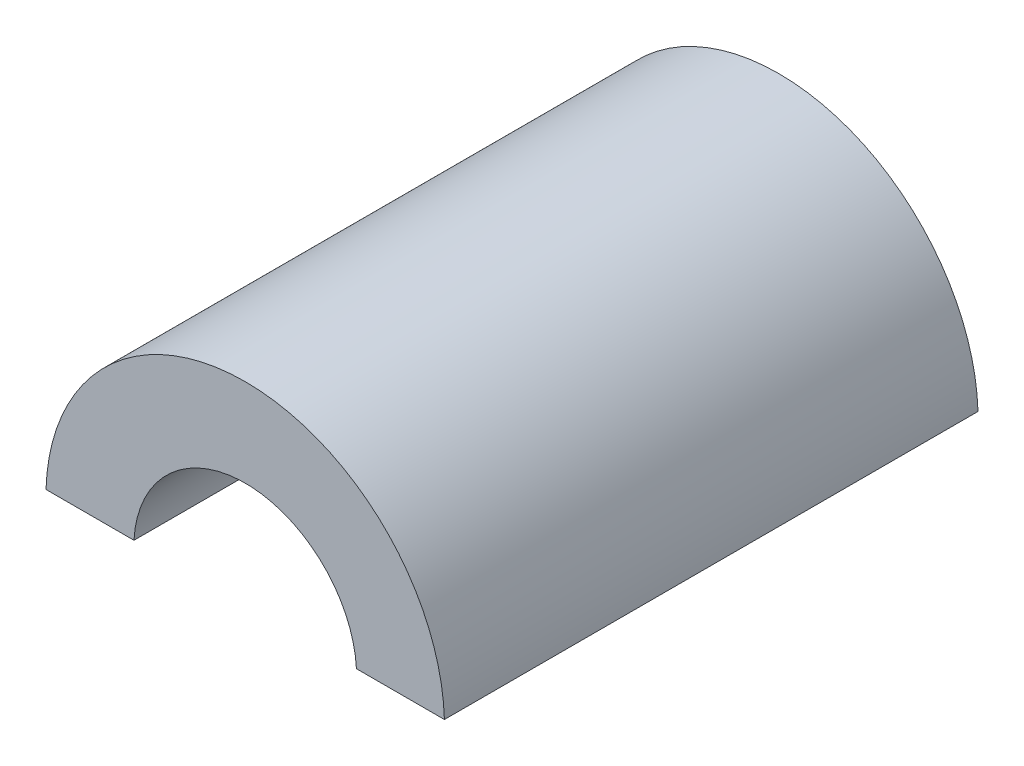
SolidWorks part; units mm, degrees
ref_plane "Front" through (0, 0, 0) normal (0, 0, 1) x (1, 0, 0)
ref_plane "Top" through (0, 0, 0) normal (0, 1, 0) x (1, 0, 0)
ref_plane "Right" through (0, 0, 0) normal (1, 0, 0) x (0, 0, -1)
sketch "Sketch1" plane through (0, 0, 0) normal (0, 0, 1) x (1, 0, 0)
  line L0 (-31.75, 0) -> (31.75, 0) construction
  line L1 (-31.7342, 1) -> (-17.7218, 1)
  line L2 (-31.75, 1) -> (31.75, 1) construction
  line L3 (17.7218, 1) -> (31.7342, 1)
  arc A0 (31.7342, 1) -> (-31.7342, 1) centre (0, 0) ccw
  arc A1 (17.7218, 1) -> (-17.7218, 1) centre (0, 0) ccw
  dimension "D1" = 35.5
  dimension "D2" = 63.5
  dimension "D3" = 1
extrude "Boss-Extrude1" add sketch "Sketch1" along normal blind 85
